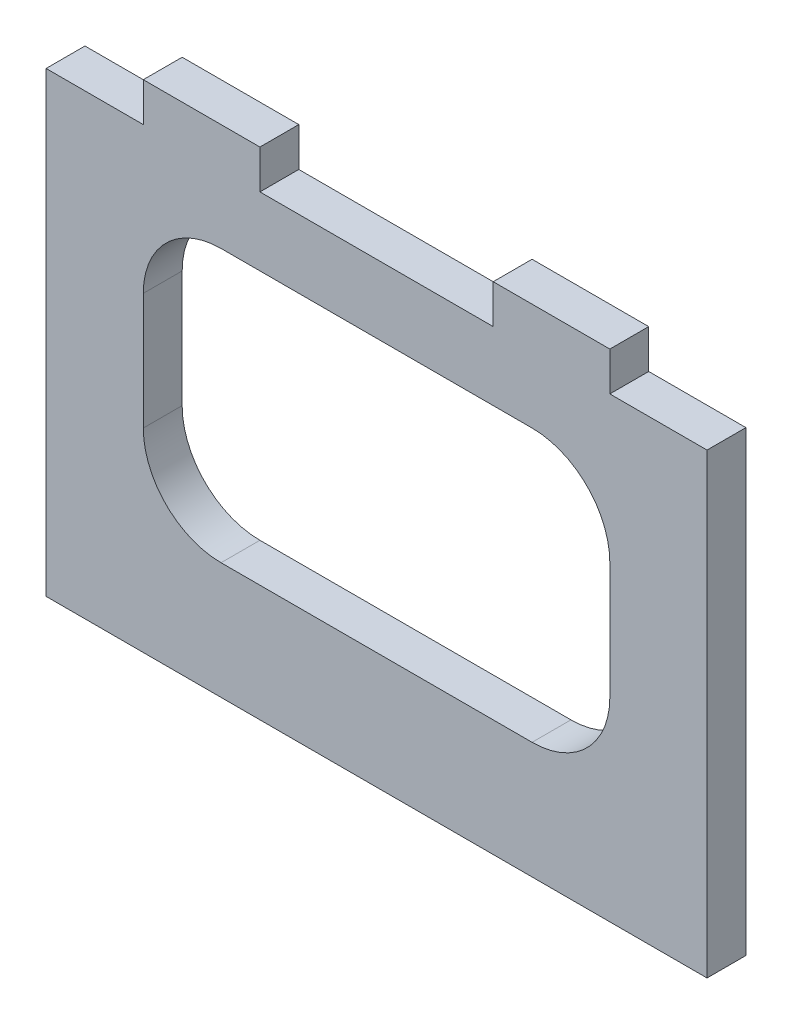
SolidWorks part; units mm, degrees
ref_plane "Ebene vorne" through (0, 0, 0) normal (0, 0, 1) x (1, 0, 0)
ref_plane "Ebene oben" through (0, 0, 0) normal (0, 1, 0) x (1, 0, 0)
ref_plane "Ebene rechts" through (0, 0, 0) normal (1, 0, 0) x (0, 0, -1)
sketch "Skizze1" plane through (0, 0, 0) normal (0, 0, 1) x (1, 0, 0)
  line L1 (0, 0) -> (85, 0)
  line L2 (0, 0) -> (0, 58.8)
  line L3 (0, 58.8) -> (85, 58.8)
  line L4 (85, 0) -> (85, 58.8)
  dimension "D1" = 85
  dimension "D2" = 58.8
extrude "Aufsatz-Linear austragen1" add sketch "Skizze1" along normal blind 5
sketch "Skizze2" plane through (0, 0, 5) normal (0, 0, 1) x (1, 0, 0)
  line L0 (42.5, 58.8) -> (42.5, 50) construction
  line L1 (12.5, 50) -> (72.5, 50)
  line L2 (12.5, 50) -> (12.5, 15)
  line L3 (12.5, 15) -> (72.5, 15)
  line L4 (72.5, 50) -> (72.5, 15)
  line L5 (85, 58.8) -> (0, 58.8) construction
  line L6 (42.5, 50) -> (42.5, 15) construction
  line L7 (42.5, 15) -> (42.5, 0) construction
  line L8 (0, 0) -> (85, 0) construction
  dimension "D1" = 35
  dimension "D2" = 60
  dimension "D3" = 15
extrude "Schnitt-Linear austragen1" cut sketch "Skizze2" against normal through all
fillet "Verrundung1" radius 10 4 edges at (12.5, 15, 2.5) (72.5, 15, 2.5) (72.5, 50, 2.5) (12.5, 50, 2.5)
sketch "Skizze3" plane through (0, 58.8, 0) normal (0, 1, 0) x (1, 0, 0)
  line L0 (42.5, 0) -> (42.5, -5) construction
  line L5 (85, 0) -> (0, 0) construction
  line L6 (85, -5) -> (0, -5) construction
  line L7 (57.5, 0) -> (57.5, -5)
  line L8 (12.5, 0) -> (27.5, 0)
  line L9 (12.5, 0) -> (12.5, -5)
  line L10 (12.5, -5) -> (27.5, -5)
  line L11 (27.5, 0) -> (27.5, -5)
  line L12 (72.5, -5) -> (57.5, -5)
  line L13 (72.5, 0) -> (72.5, -5)
  line L14 (72.5, 0) -> (57.5, 0)
  dimension "D1" = 15
  dimension "D2" = 30
extrude "Aufsatz-Linear austragen2" add sketch "Skizze3" along normal blind 5
